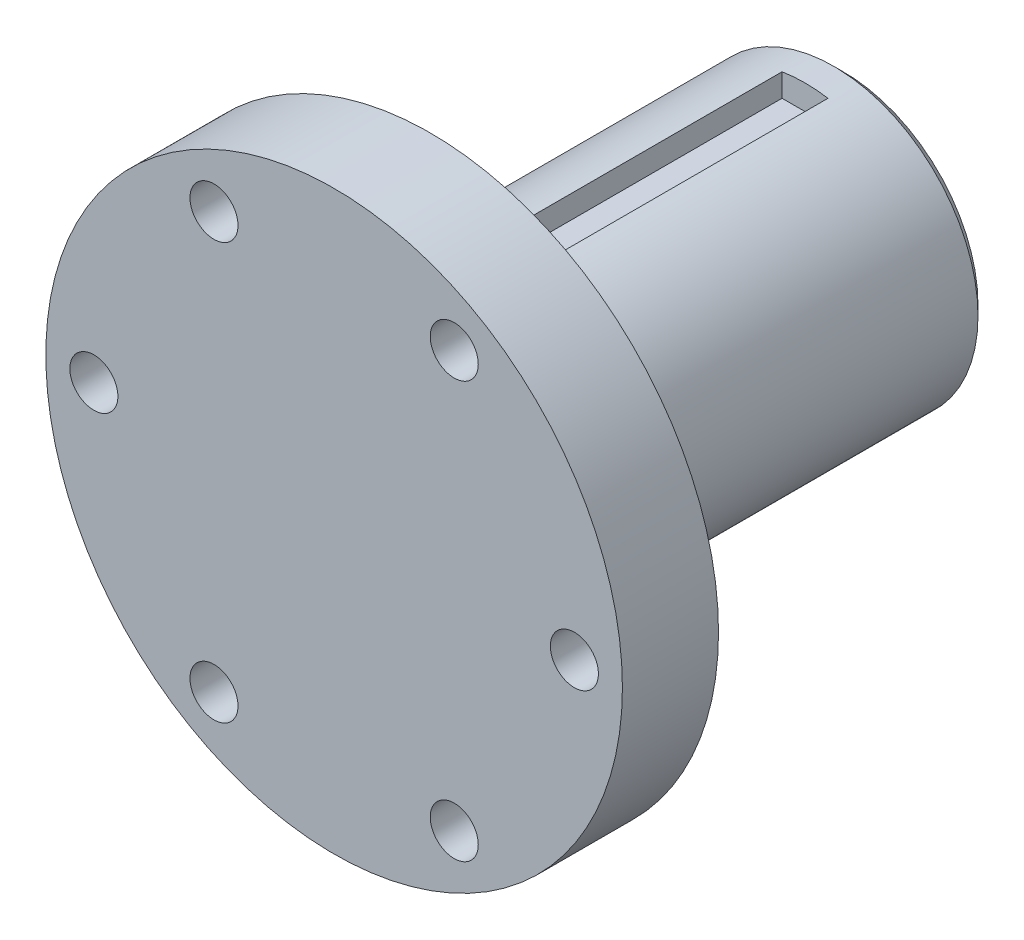
SolidWorks part; units mm, degrees
ref_plane "Płaszczyzna przednia" through (0, 0, 0) normal (0, 0, 1) x (1, 0, 0)
ref_plane "Płaszczyzna górna" through (0, 0, 0) normal (0, 1, 0) x (1, 0, 0)
ref_plane "Płaszczyzna prawa" through (0, 0, 0) normal (1, 0, 0) x (0, 0, -1)
sketch "Szkic1" plane through (0, 0, 0) normal (0, 0, 1) x (1, 0, 0)
  circle A0 centre (0, 0) radius 15
  dimension "D1" = 30
extrude "Dodanie-wyciągnięcie1" add sketch "Szkic1" along normal blind 53 contours A0
ref_plane "Płaszczyzna1" through (0, 0, 4) normal (0, 0, -1) x (-1, 0, 0)
chamfer "Sfazowanie1" distance 1 angle 45 1 edges at (15, 0, 0)
sketch "Szkic2" plane through (0, 0, 4) normal (0, 0, -1) x (-1, 0, 0)
  line L0 (-2.39, 14.8084) -> (-2.39, 12.4184)
  line L1 (-2.39, 12.4184) -> (2.39, 12.4184)
  line L2 (2.39, 12.4184) -> (2.39, 14.8084)
  circle A0 centre (0, 0) radius 15 construction
  arc A1 (2.39, 14.8084) -> (-2.39, 14.8084) centre (0, 0) ccw
  point P5 (0, 12.4184)
  dimension "D1" = 4.78
  dimension "D2" = 2.39
extrude "Wytnij-wyciągnięcie1" cut sketch "Szkic2" against normal blind 35
sketch "Szkic3" plane through (0, 0, 53) normal (0, 0, 1) x (1, 0, 0)
  circle A0 centre (0, 0) radius 30
  dimension "D1" = 60
extrude "Dodanie-wyciągnięcie2" add sketch "Szkic3" against normal blind 10
sketch "Szkic4" plane through (0, 0, 43) normal (0, 0, -1) x (-1, 0, 0)
  circle A0 centre (-25, 0) radius 2.5
  point P2 (0, 0)
  point P5 (-22.1163, 0)
  dimension "D1" = 5
  dimension "D2" = 25
extrude "Wytnij-wyciągnięcie2" cut sketch "Szkic4" against normal through all
pattern_circular "Szyk kołowy1" count 6 over 360 about axis through (0, 0, 0) along (0, 0, 1) of "Wytnij-wyciągnięcie2"
